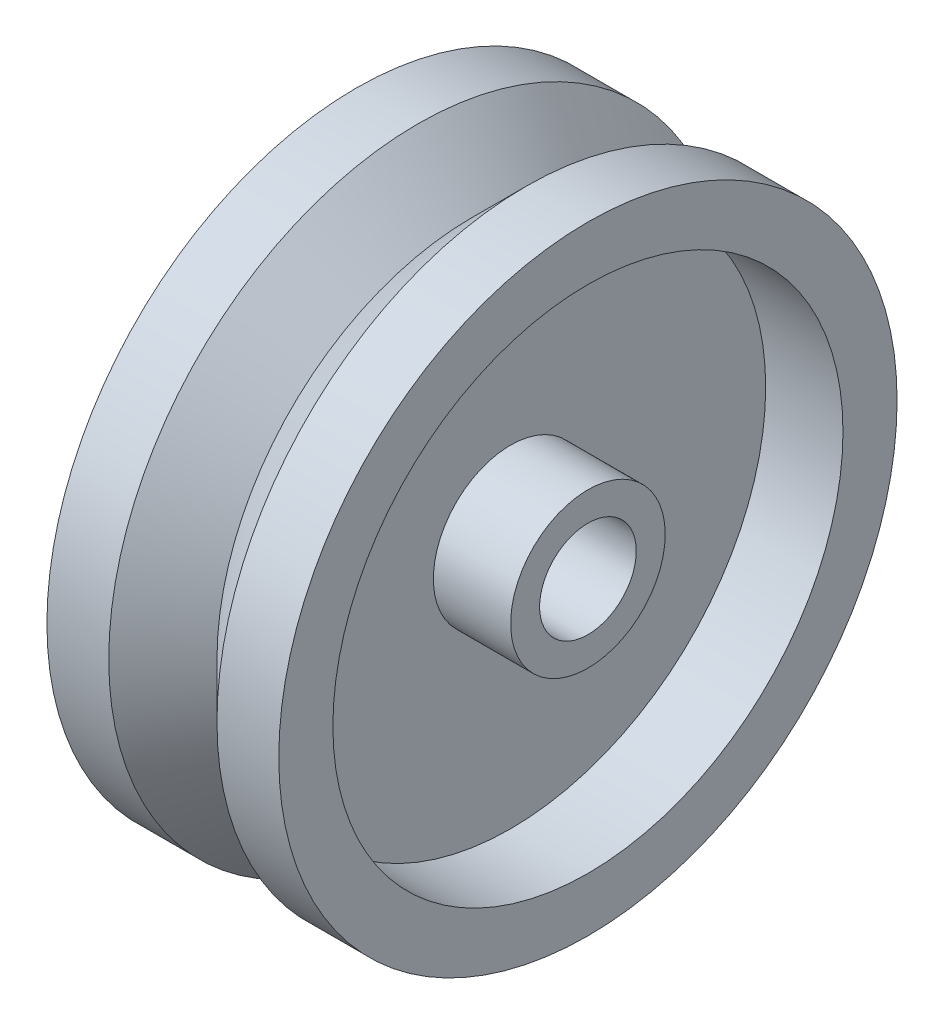
SolidWorks part; units mm, degrees
ref_plane "Front Plane" through (0, 0, 0) normal (0, 0, 1) x (1, 0, 0)
ref_plane "Top Plane" through (0, 0, 0) normal (0, 1, 0) x (1, 0, 0)
ref_plane "Right Plane" through (0, 0, 0) normal (1, 0, 0) x (0, 0, -1)
sketch "Sketch1" plane through (0, 0, 0) normal (1, 0, 0) x (0, 0, -1)
  circle A0 centre (0, 0) radius 20
  circle A1 centre (0, 0) radius 3.125
  dimension "D1" = 40
  dimension "D2" = 6.25
extrude "Boss-Extrude1" add sketch "Sketch1" along normal mid plane 15
sketch "Sketch2" plane through (7.5, 0, 0) normal (1, 0, 0) x (0, 0, -1)
  circle A0 centre (0, 0) radius 16.5
  circle A1 centre (0, 0) radius 5
  dimension "D1" = 33
  dimension "D2" = 10
extrude "Cut-Extrude1" cut sketch "Sketch2" against normal blind 5
mirror "Mirror1" about plane through (0, 0, 0) normal (1, 0, 0) of "Cut-Extrude1"
sketch "Sketch3" plane through (0, 0, 0) normal (0, 0, 1) x (1, 0, 0)
  line L0 (-3.5, 20) -> (3.5, 20)
  line L1 (7.5, 20) -> (-7.5, 20) construction
  line L2 (3.5, 20) -> (0, 16.5)
  line L3 (0, 16.5) -> (-3.5, 20)
  line L4 (0, 0) -> (0, 12.0382) construction
  line L5 (-7.5, 20) -> (-7.5, -20) construction
  line L6 (7.5, -20) -> (7.5, 20) construction
  line L7 (0, 0) -> (5.0756, 0) construction
  dimension "D1" = 90
  dimension "D2" = 4
  dimension "D3" = 4
revolve "Cut-Revolve1" cut sketch "Sketch3" angle 360 about L7
